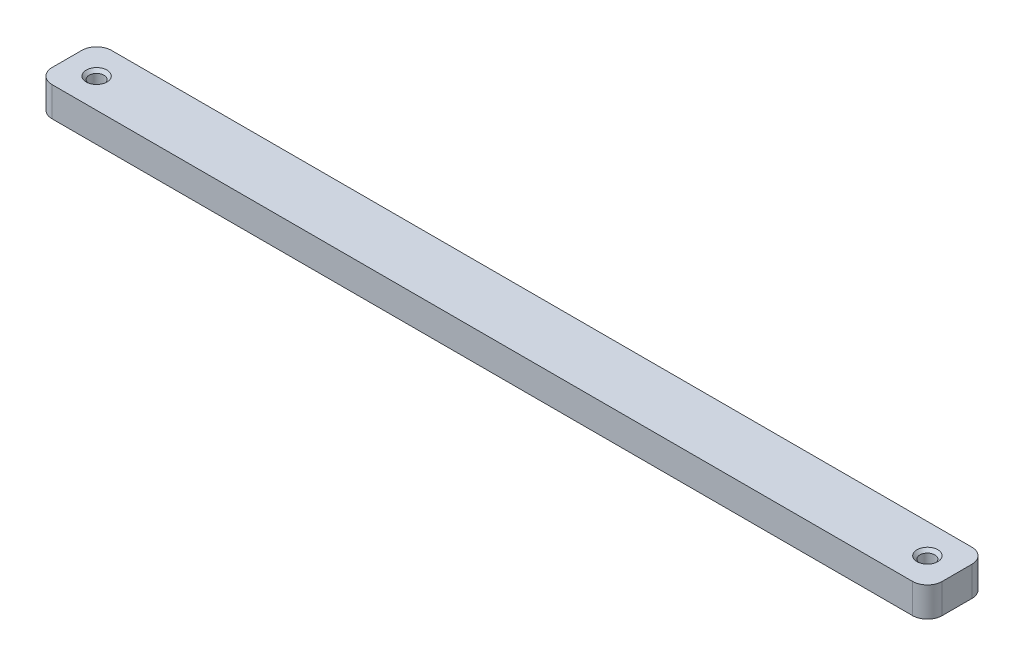
SolidWorks part; units mm, degrees
material "Acciaio al carbonio semplice"
ref_plane "Piano frontale" through (0, 0, 0) normal (0, 0, 1) x (1, 0, 0)
ref_plane "Piano superiore" through (0, 0, 0) normal (0, 1, 0) x (1, 0, 0)
ref_plane "Piano destro" through (0, 0, 0) normal (1, 0, 0) x (0, 0, -1)
sketch "Schizzo1" plane through (0, 0, 0) normal (0, 1, 0) x (1, 0, 0)
  line L1 (150, -10) -> (-150, -10)
  line L2 (150, -10) -> (150, 10)
  line L3 (150, 10) -> (-150, 10)
  line L4 (-150, -10) -> (-150, 10)
  line L5 (150, -10) -> (-150, 10) construction
  line L6 (150, 10) -> (-150, -10) construction
  point P0 (0, 0)
  dimension "D1" = 20
  dimension "D2" = 300
extrude "Estrusione-Estrusione1" add sketch "Schizzo1" along normal blind 10
hole_wizard "Foro filettato M6-1" positions "Schizzo3" profile "Schizzo2" tap size "M6" standard "ISO"
sketch "Schizzo3" plane through (0, 10, 0) normal (0, 1, 0) x (-1, 0, 0)
  line L0 (-150, 10) -> (-150, -10) construction
  line L1 (150, -10) -> (150, 10) construction
  point P0 (140, 0)
  point P1 (-140, 0)
  dimension "D1" = 10
  dimension "D2" = 10
sketch "Schizzo2" plane through (-140, 10, 0) normal (1, 0, 0) x (0, 0, 1)
  line L0 (0, 0) -> (0, 12.5022)
  line L1 (0, 12.5022) -> (2.5, 11)
  line L2 (2.5, 11) -> (2.5, 1)
  line L3 (2.5, 1) -> (3.5, 0)
  line L5 (3.5, 0) -> (0, 0)
  line L6 (-2.5, 1) -> (-3.5, 0) construction
  line L10 (0, 12.5022) -> (-2.5, 11) construction
  line L11 (0, -6.35) -> (0, 107.95) construction
  dimension "Tap Drill Dia." = 5
  dimension "Tap Drill Depth" = 11
  dimension "Near C'Sink Dia." = 7
  dimension "Near C'Sink Angle" = 90
  dimension "Drill Angle" = 118
cosmetic thread "Filettatura del foro1" parameters "D1"=6, "D2"=6
cosmetic thread "Filettatura del foro2" parameters "D1"=6, "D2"=6
fillet "Raccordo1" radius 5 4 edges at (-150, 5, 10) (-150, 5, -10) (150, 5, 10) (150, 5, -10)
